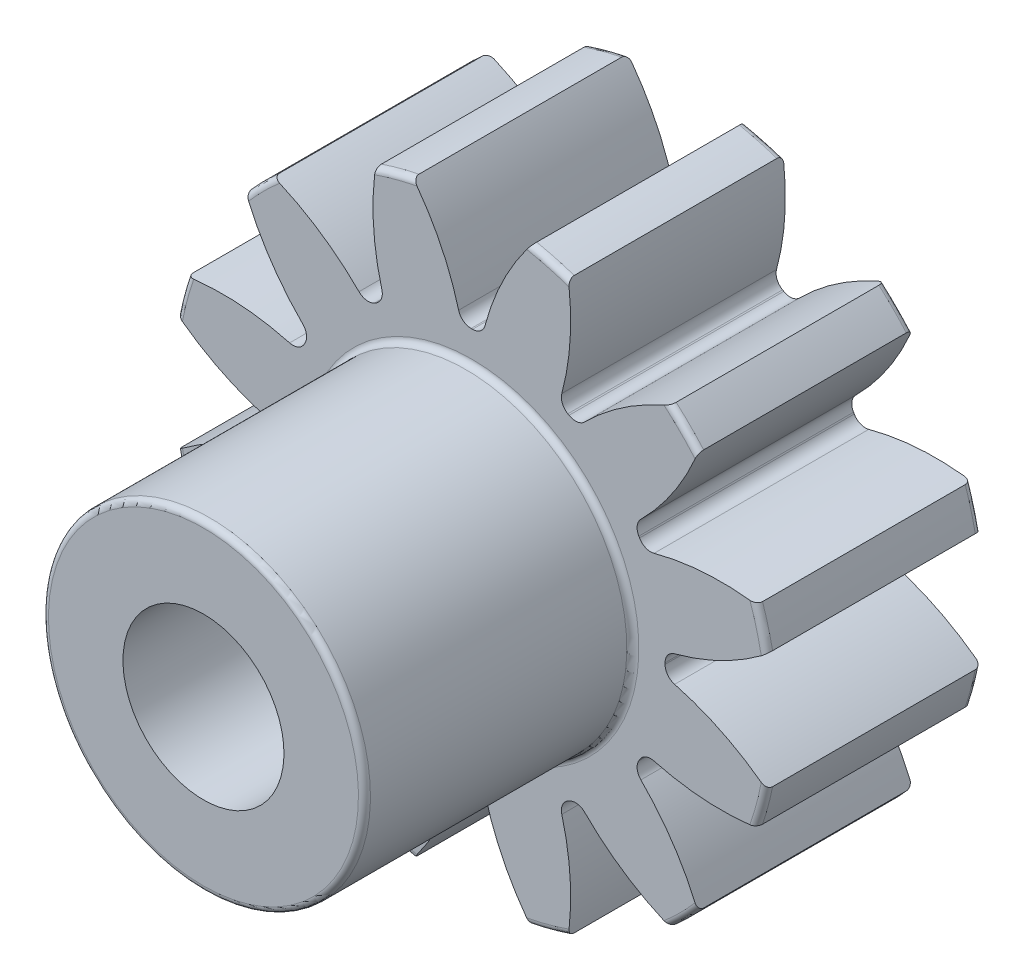
SolidWorks part; units mm, degrees
ref_plane "Front Plane" through (0, 0, 0) normal (0, 0, 1) x (1, 0, 0)
ref_plane "Top Plane" through (0, 0, 0) normal (0, 1, 0) x (1, 0, 0)
ref_plane "Right Plane" through (0, 0, 0) normal (1, 0, 0) x (0, 0, -1)
sketch "Sketch1" plane through (0, 0, 0) normal (0, 0, 1) x (1, 0, 0)
  line L0 (-152.4, 0) -> (152.4, 0) construction
  circle A0 centre (0, 0) radius 5.6 construction
  circle A1 centre (0, 0) radius 4.8 construction
  circle A2 centre (0, 0) radius 3.6 construction
  circle A3 centre (0, 0) radius 3 construction
  circle A4 centre (0, 0) radius 1.5 construction
  dimension "D2" = 0.8
  dimension "D3" = 2
  dimension "D1" = 2
sketch "Sketch2" plane through (0, 0, 0) normal (1, 0, 0) x (0, 0, -1)
  line L0 (0, 0) -> (-4, 0) construction
  line L1 (-4, 0) -> (-9, 0) construction
  dimension "Overall Width" = 9
  dimension "Face Width" = 4
sketch "Sketch4" plane through (0, 0, 0) normal (1, 0, 0) x (0, 0, -1)
  line L0 (-9, 1.5) -> (-9, 3)
  line L1 (-9, 3) -> (-4, 3)
  line L2 (-4, 3) -> (-4, 5.6)
  line L3 (-4, 5.6) -> (0, 5.6)
  line L4 (0, 5.6) -> (0, 1.5)
  line L5 (-4, 3) -> (-4, 0) construction
  line L6 (0, 5.6) -> (0, -5.6) construction
  line L7 (-4, 3) -> (0, 3) construction
  line L12 (-9, 1.5) -> (0, 1.5)
revolve "Revolve1" add sketch "Sketch4" angle 360 about L1
fillet "Fillet2" radius 0.112 4 edges at (0, 3, 9) (0, 3, 4) (0, 5.6, 4) (0, 5.6, 0)
sketch "Sketch7" plane through (0, 0, 4) normal (0, 0, 1) x (1, 0, 0)
  line L0 (0, 0) -> (0, 5.6) construction
  line L1 (0.6265, 4.7589) -> (1.016, 5.5071) construction
  line L3 (1.4494, 5.4092) -> (1.2423, 4.6364) construction
  line L4 (1.2423, 4.6364) -> (0.9317, 3.4773) construction
  line L5 (0, 0) -> (0.9317, 3.4773) construction
  line L6 (0.6265, 4.7589) -> (0, 0) construction
  line L7 (0.6265, 4.7589) -> (0.7309, 5.5521) construction
  line L8 (0.6265, 4.7589) -> (0, 0) construction
  circle A0 centre (0, 0) radius 5.6 construction
  arc A1 (-0.0131, 3.6) -> (0.0131, 3.6) centre (0, 0) cw
  circle A2 centre (0, 0) radius 3.6 construction
  arc A3 (-0.6265, 4.7589) -> (0.6265, 4.7589) centre (0, 0) cw construction
  circle A4 centre (0, 0) radius 4.8 construction
  arc A5 (1.7958, 5.3042) -> (1.0969, 5.4915) centre (0, 0) ccw construction
  arc A6 (0.6265, 4.7589) -> (1.8369, 4.4346) centre (0, 0) cw construction
  arc A7 (-1.0969, 5.4915) -> (1.0969, 5.4915) centre (0, 0) cw
  arc A8 (0.246, 3.7782) -> (1.0969, 5.4915) centre (4.8842, 2.5425) cw
  arc A9 (-0.246, 3.7782) -> (-1.0969, 5.4915) centre (-4.8842, 2.5425) ccw
  arc A10 (-0.0131, 3.6) -> (-0.246, 3.7782) centre (-0.014, 3.84) cw
  arc A11 (0.0131, 3.6) -> (0.246, 3.7782) centre (0.014, 3.84) ccw
  point P26 (-0.2008, 3.5944)
  point P29 (0.2008, 3.5944)
  dimension "D4" = 0.24
  dimension "D5" = 4.8
  dimension "D3" = 20
  dimension "D1" = 2.5133
  dimension "D2" = 1.2566
extrude "Cut-Extrude2" cut sketch "Sketch7" against normal through all
pattern_circular "CirPattern1" count 12 over 360 about axis through (0, 0, 0) along (0, 0, 1) of "Cut-Extrude2"
equation "\"D1@Sketch1\"=2.5*(\"Pitch Dia.@Sketch1\"/\"Number of Teeth@Sketch1\")"
equation "\"D1@CirPattern1\"=\"Number of Teeth@Sketch1\""
equation "\"D1@Fillet2\"=\"OD@Sketch1\"*.01"
equation "\"D1@Sketch7\"=3.14159*(\"Pitch Dia.@Sketch1\"/\"Number of Teeth@Sketch1\")"
equation "\"D2@Sketch7\"=\"D1@Sketch7\"/2"
equation "\"D4@Sketch7\"=\"D1@Sketch7\"*.0955"
equation "\"D5@Sketch7\"=\"Pitch Dia.@Sketch1\"/2"
